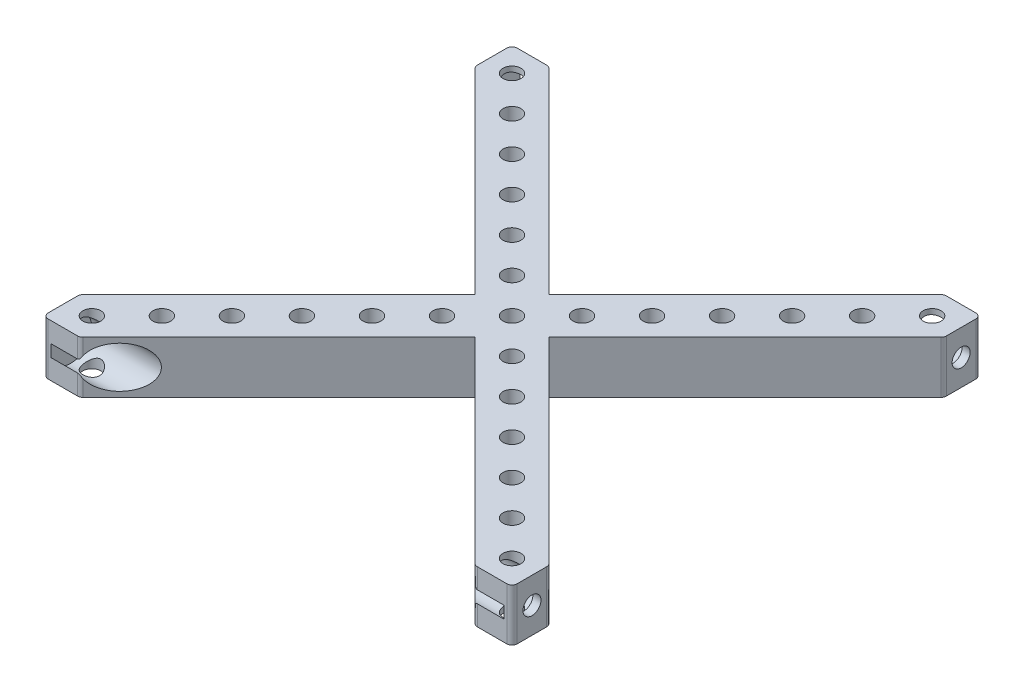
SolidWorks part; units mm, degrees
ref_plane "Front Plane" through (0, 0, 0) normal (0, 0, 1) x (1, 0, 0)
ref_plane "Top Plane" through (0, 0, 0) normal (0, 1, 0) x (1, 0, 0)
ref_plane "Right Plane" through (0, 0, 0) normal (1, 0, 0) x (0, 0, -1)
sketch "Sketch1" plane through (0, 0, 0) normal (0, 1, 0) x (1, 0, 0)
  line L0 (-45, 45) -> (-45, -45) construction
  line L1 (45, 45) -> (45, -45) construction
  line L2 (-45, 45) -> (45, 45) construction
  line L3 (45, -45) -> (-45, -45) construction
  line L4 (-45, -45) -> (45, 45) construction
  line L5 (-45, 45) -> (45, -45) construction
  line L6 (-45, 37.9289) -> (37.9289, -45)
  line L7 (-37.9289, 45) -> (45, -37.9289)
  line L8 (-37.9289, -45) -> (45, 37.9289)
  line L9 (-45, -37.9289) -> (37.9289, 45)
  line L10 (-45, 45) -> (-37.9289, 45)
  line L11 (-45, 45) -> (-45, 37.9289)
  line L12 (-45, -37.9289) -> (-45, -45)
  line L13 (-45, -45) -> (-37.9289, -45)
  line L14 (37.9289, -45) -> (45, -45)
  line L15 (45, -45) -> (45, -37.9289)
  line L16 (45, 37.9289) -> (45, 45)
  line L17 (45, 45) -> (37.9289, 45)
  line L18 (-41.4645, 48.5355) -> (48.5355, -41.4645) construction
  line L19 (-48.5355, 41.4645) -> (41.4645, -48.5355) construction
  line L20 (-48.5355, -41.4645) -> (41.4645, 48.5355) construction
  line L21 (-41.4645, -48.5355) -> (48.5355, 41.4645) construction
  circle A0 centre (0, 0) radius 1.725
  circle A1 centre (6.7175, -6.7175) radius 1.725
  circle A2 centre (13.435, -13.435) radius 1.725
  circle A3 centre (20.1525, -20.1525) radius 1.725
  circle A4 centre (26.8701, -26.8701) radius 1.725
  circle A5 centre (33.5876, -33.5876) radius 1.725
  circle A6 centre (40.3051, -40.3051) radius 1.725
  circle A7 centre (-6.7175, -6.7175) radius 1.725
  circle A8 centre (-20.1525, -20.1525) radius 1.725
  circle A9 centre (-13.435, -13.435) radius 1.725
  circle A10 centre (-26.8701, -26.8701) radius 1.725
  circle A11 centre (-33.5876, -33.5876) radius 1.725
  circle A12 centre (-40.3051, -40.3051) radius 1.725
  circle A13 centre (-6.7175, 6.7175) radius 1.725
  circle A14 centre (-20.1525, 20.1525) radius 1.725
  circle A15 centre (-13.435, 13.435) radius 1.725
  circle A16 centre (-26.8701, 26.8701) radius 1.725
  circle A17 centre (-33.5876, 33.5876) radius 1.725
  circle A18 centre (-40.3051, 40.3051) radius 1.725
  circle A19 centre (6.7175, 6.7175) radius 1.725
  circle A20 centre (20.1525, 20.1525) radius 1.725
  circle A21 centre (13.435, 13.435) radius 1.725
  circle A22 centre (26.8701, 26.8701) radius 1.725
  circle A23 centre (33.5876, 33.5876) radius 1.725
  circle A24 centre (40.3051, 40.3051) radius 1.725
  point P2 (-45, 0)
  point P75 (0, 0)
  dimension "D8" = 3.45
  dimension "D9" = 7
  dimension "D1" = 45
  dimension "D2" = 45
  dimension "D3" = 90
  dimension "D4" = 5
  dimension "D5" = 5
  dimension "D6" = 5
  dimension "D7" = 5
  dimension "D10" = 4
extrude "Boss-Extrude1" add sketch "Sketch1" along normal blind 10 contours L10 L11 L6 L9 L7 A18 A17 A16 A15 A14 A13 | L16 L17 L9 L7 L8 A24 A23 A22 A21 A20 A19 | L9 L6 L8 L7 A0 | L14 L15 L7 L8 L6 A6 A5 A4 A3 A2 A1 | L12 L13 L8 L6 L9 A12 A11 A10 A9 A8 A7
fillet "Fillet1" radius 1 12 edges at (37.9289, 5, -45) (45, 5, -45) (45, 5, -37.9289) (45, 5, 37.9289) (45, 5, 45) (37.9289, 5, 45) (-37.9289, 5, 45) (-45, 5, 45) (-45, 5, 37.9289) (-45, 5, -37.9289) (-37.9289, 5, -45) (-45, 5, -45)
sketch "Sketch2" plane through (-45, 0, 0) normal (-1, 0, 0) x (0, 0, 1)
  line L0 (-62.6005, 5) -> (62.6005, 5) construction
  line L1 (-37.9289, 10) -> (-37.9289, 0) construction
  line L2 (-44, 10) -> (-38.3431, 10) construction
  line L3 (38.3431, 10) -> (44, 10) construction
  circle A0 centre (-41.1716, 5) radius 1.725
  circle A1 centre (41.1716, 5) radius 1.725
  point P3 (0, 5)
  point P6 (-37.9289, 5)
  point P11 (-41.1716, 10)
  point P15 (41.1716, 10)
  dimension "D1" = 3.45
  dimension "D2" = 3.45
extrude "Cut-Extrude2" cut sketch "Sketch2" against normal blind 1.55
sketch "Sketch3" plane through (-43.45, 0, 0) normal (-1, 0, 0) x (0, 0, 1)
  circle A0 centre (-41.1716, 5) radius 4
  circle A1 centre (41.1716, 5) radius 4
  dimension "D1" = 8
  dimension "D2" = 8
extrude "Cut-Extrude3" cut sketch "Sketch3" against normal blind 40
mirror "Mirror1" about plane through (0, 0, 0) normal (1, 0, 0) of "Cut-Extrude3", "Cut-Extrude2"
equation "\"D2@Sketch2\"=\"D1@Sketch2\""
equation "\"D2@Sketch3\"=\"D1@Sketch3\""
